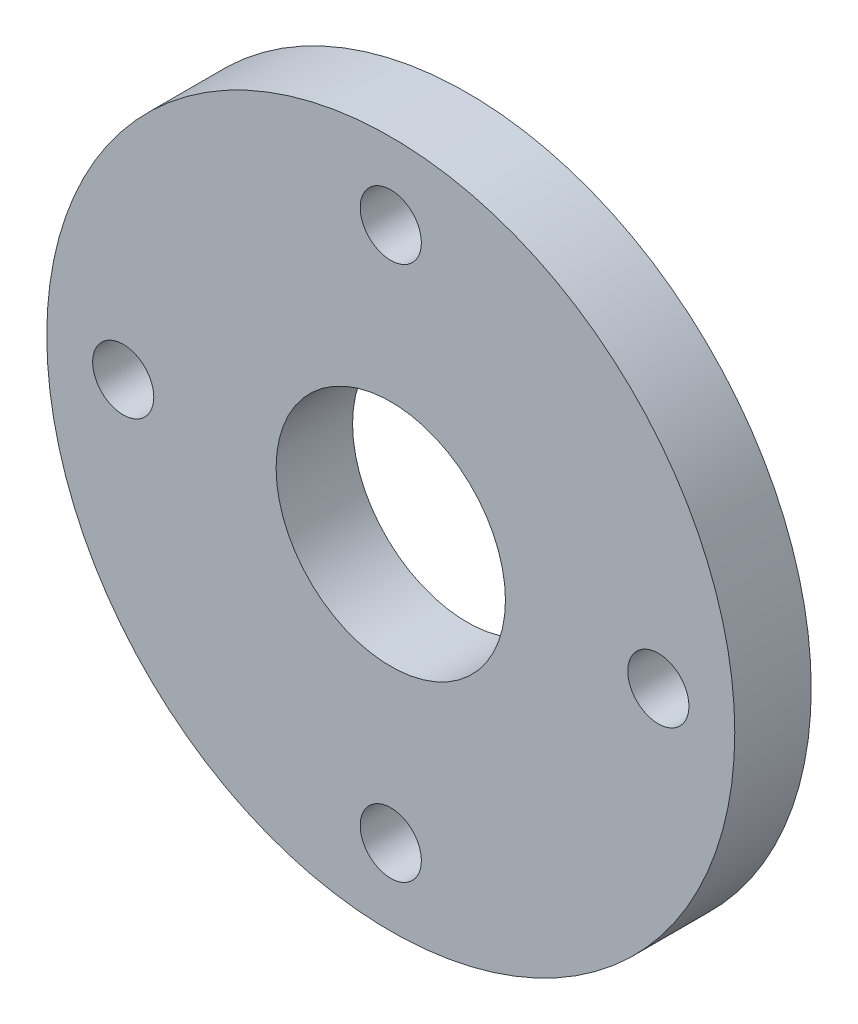
SolidWorks part; units mm, degrees
material "POM 乙缩醛共聚物"
ref_plane "前视基准面" through (0, 0, 0) normal (0, 0, 1) x (1, 0, 0)
ref_plane "上视基准面" through (0, 0, 0) normal (0, 1, 0) x (1, 0, 0)
ref_plane "右视基准面" through (0, 0, 0) normal (1, 0, 0) x (0, 0, -1)
sketch "草图1" plane through (0, 0, 0) normal (0, 0, 1) x (1, 0, 0)
  circle A0 centre (0, 0) radius 22.5
  dimension "D1" = 45
extrude "凸台-拉伸1" add sketch "草图1" along normal blind 5
sketch "草图2" plane through (0, 0, 5) normal (0, 0, 1) x (1, 0, 0)
  circle A0 centre (0, 0) radius 7.5
  dimension "D1" = 15
extrude "切除-拉伸1" cut sketch "草图2" against normal through all
sketch "草图3" plane through (0, 0, 5) normal (0, 0, 1) x (1, 0, 0)
  circle A0 centre (0, 0) radius 17.5 construction
  circle A1 centre (-17.5, 0) radius 2
  circle A2 centre (0, -17.5) radius 2
  circle A3 centre (17.5, 0) radius 2
  circle A4 centre (0, 17.5) radius 2
  dimension "D1" = 35
  dimension "D2" = 4
extrude "切除-拉伸2" cut sketch "草图3" against normal through all and the other way through all
